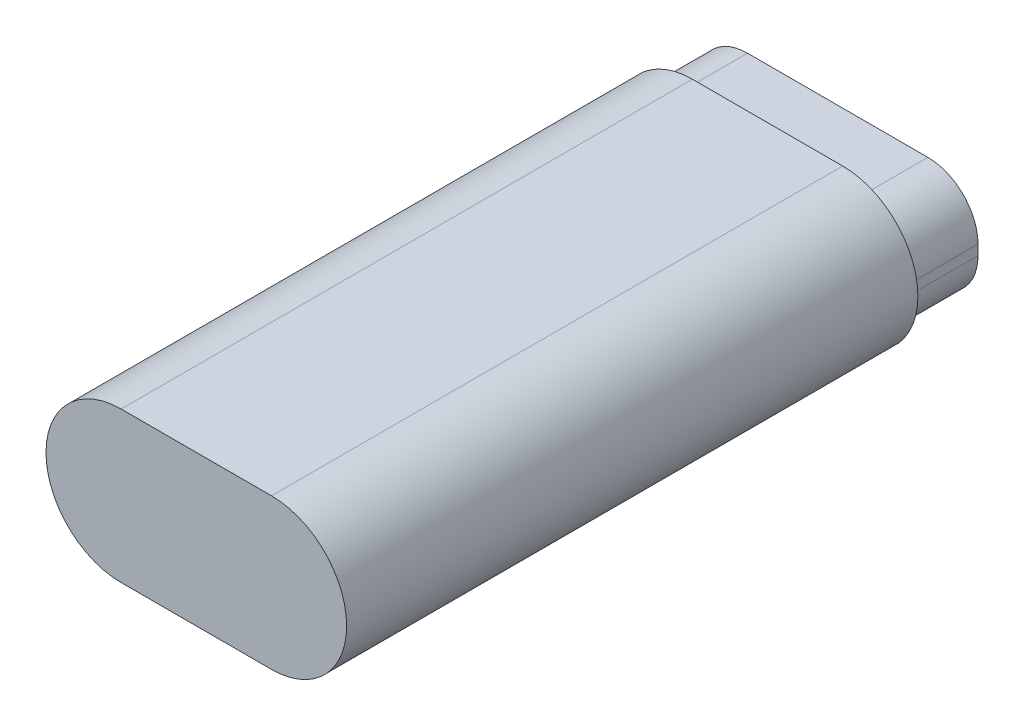
SolidWorks part; units mm, degrees
ref_plane "Front Plane" through (0, 0, 0) normal (0, 0, 1) x (1, 0, 0)
ref_plane "Top Plane" through (0, 0, 0) normal (0, 1, 0) x (1, 0, 0)
ref_plane "Right Plane" through (0, 0, 0) normal (1, 0, 0) x (0, 0, -1)
sketch "Sketch1" plane through (0, 0, 0) normal (0, 0, 1) x (1, 0, 0)
  line L0 (0, 0) -> (15, 0) construction
  line L1 (0, 7.5) -> (15, 7.5)
  line L2 (0, -7.5) -> (15, -7.5)
  arc A0 (0, 7.5) -> (0, -7.5) centre (0, 0) ccw
  arc A1 (15, -7.5) -> (15, 7.5) centre (15, 0) ccw
  point P3 (7.5, 0)
  dimension "D1" = 7.5
  dimension "D2" = 15
extrude "Boss-Extrude1" add sketch "Sketch1" along normal blind 57
sketch "Sketch3" plane through (0, 0, 0) normal (0, 0, -1) x (-1, 0, 0)
  line L0 (-15, 7.5) -> (0, 7.5) construction
  line L1 (-16.5, 5.5) -> (1.5, 5.5)
  line L2 (-21.5, 0.5) -> (-21.5, -0.5)
  line L3 (-16.5, -5.5) -> (1.5, -5.5)
  line L4 (6.5, 0.5) -> (6.5, -0.5)
  line L5 (0, -7.5) -> (-15, -7.5) construction
  arc A1 (0, -7.5) -> (0, 7.5) centre (0, 0) ccw construction
  arc A2 (-15, 7.5) -> (-15, -7.5) centre (-15, 0) ccw construction
  arc A3 (1.5, -5.5) -> (6.5, -0.5) centre (1.5, -0.5) ccw
  arc A4 (1.5, 5.5) -> (6.5, 0.5) centre (1.5, 0.5) cw
  arc A5 (-16.5, 5.5) -> (-21.5, 0.5) centre (-16.5, 0.5) ccw
  arc A6 (-21.5, -0.5) -> (-16.5, -5.5) centre (-16.5, -0.5) ccw
  point P8 (7.5, 0)
  point P12 (-22.5, 0)
  dimension "D5" = 5
  dimension "D1" = 2
  dimension "D2" = 2
  dimension "D3" = 1
  dimension "D4" = 1
extrude "Boss-Extrude2" add sketch "Sketch3" along normal blind 7
